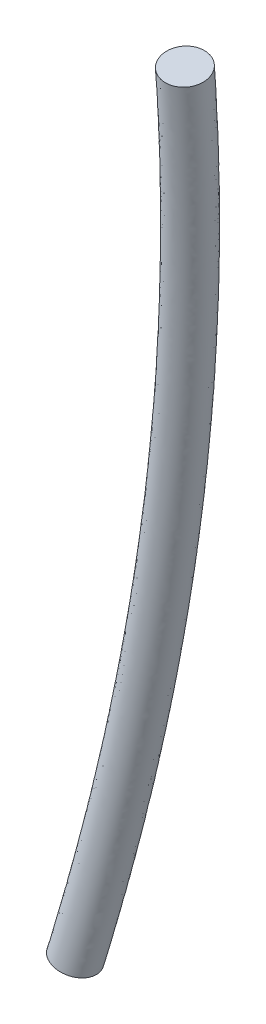
SolidWorks part; units mm, degrees
material "Custom Plastic"
ref_plane "X-Y Datum" through (0, 0, 0) normal (0, 0, 1) x (1, 0, 0)
ref_plane "X-Z Datum" through (0, 0, 0) normal (0, 1, 0) x (1, 0, 0)
ref_plane "Y-Z Datum" through (0, 0, 0) normal (1, 0, 0) x (0, 0, -1)
sketch3d "3DSketch1"
  circle A0 centre (-19, -40.3793, 237.3572) radius 2.286 construction
  circle A1 centre (-38.9257, -165.2645, 232.3735) radius 4.5 construction
  spline S0 degree 2 poles (-19, -40.3793, 237.3572) (-24.1775, -106.7506, 227.7028) (-40.2627, -170.658, 232.775) knots 0 0 0 1 1 1
  point P8 (-19, -42.6653, 237.3572)
  point P11 (-38.1443, -160.8329, 232.3735)
sweep "Sweep1" add path "3DSketch1" circular profile diameter 6.35 parameters "D3"=6.35
